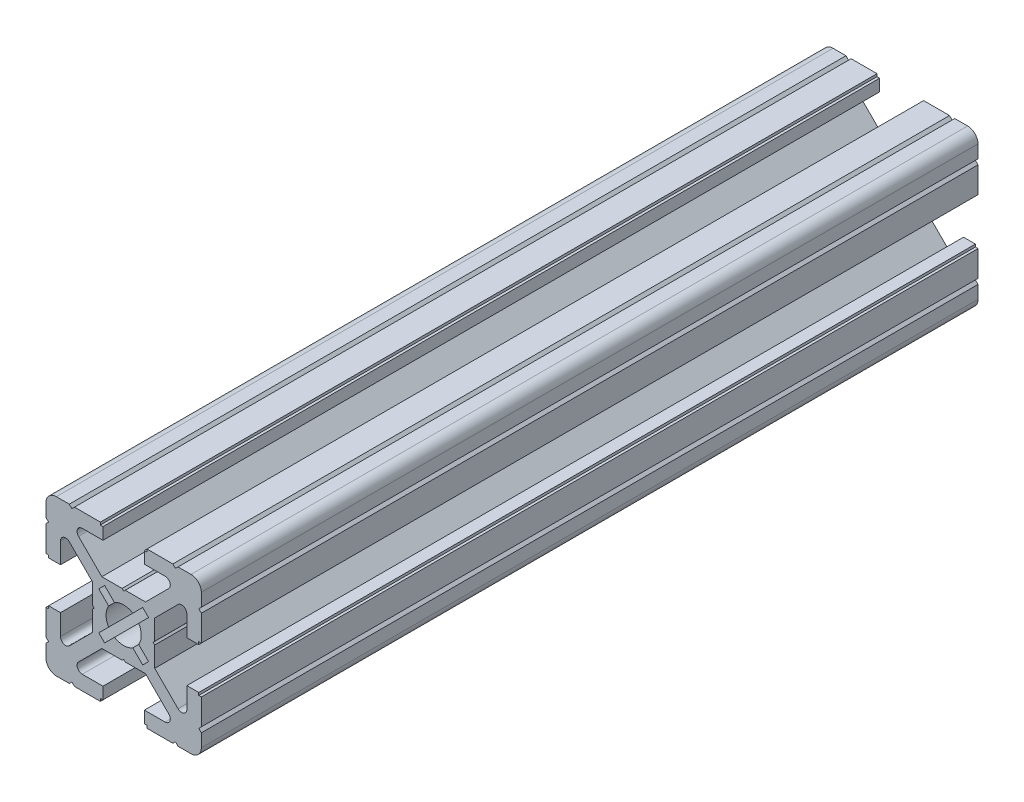
SolidWorks part; units mm, degrees
material "1060 Alloy"
ref_plane "Front" through (0, 0, 0) normal (0, 0, 1) x (1, 0, 0)
ref_plane "Top" through (0, 0, 0) normal (0, 1, 0) x (1, 0, 0)
ref_plane "Right" through (0, 0, 0) normal (1, 0, 0) x (0, 0, -1)
sketch "Sketch1" plane through (0, 0, 0) normal (0, 0, 1) x (1, 0, 0)
  line L0 (-2.9023, 1.771) -> (-4.8083, 3.677)
  line L1 (-4.8083, 3.677) -> (-3.677, 4.8083)
  line L2 (-3.677, 4.8083) -> (-1.771, 2.9023)
  line L3 (1.771, 2.9023) -> (3.677, 4.8083)
  line L4 (3.677, 4.8083) -> (4.8083, 3.677)
  line L5 (4.8083, 3.677) -> (2.9023, 1.771)
  line L6 (2.9023, -1.771) -> (4.8083, -3.677)
  line L7 (4.8083, -3.677) -> (3.677, -4.8083)
  line L8 (3.677, -4.8083) -> (1.771, -2.9023)
  line L9 (-1.771, -2.9023) -> (-3.677, -4.8083)
  line L10 (-3.677, -4.8083) -> (-4.8083, -3.677)
  line L11 (-4.8083, -3.677) -> (-2.9023, -1.771)
  line L12 (13, 15) -> (10.5, 15)
  line L13 (10.5, 15) -> (10, 14.5)
  line L14 (10, 14.5) -> (9.5, 15)
  line L15 (9.5, 15) -> (4.5, 15)
  line L16 (4.5, 15) -> (4.5, 14.5)
  line L17 (4.5, 14.5) -> (4, 14.5)
  line L18 (4, 14.5) -> (4, 12.2)
  line L19 (4, 12.2) -> (8, 12.2)
  line L20 (8.7071, 10.4929) -> (4.2142, 6)
  line L21 (4.2142, 6) -> (0.3125, 6)
  line L22 (0.3125, 6) -> (0, 5.7)
  line L23 (0, 5.7) -> (-0.3125, 6)
  line L24 (-0.3125, 6) -> (-4.2142, 6)
  line L25 (-4.2142, 6) -> (-8.7071, 10.4929)
  line L26 (-8, 12.2) -> (-4, 12.2)
  line L27 (-4, 12.2) -> (-4, 14.5)
  line L28 (-4, 14.5) -> (-4.5, 14.5)
  line L29 (-4.5, 14.5) -> (-4.5, 15)
  line L30 (-4.5, 15) -> (-9.5, 15)
  line L31 (-9.5, 15) -> (-10, 14.5)
  line L32 (-10, 14.5) -> (-10.5, 15)
  line L33 (-10.5, 15) -> (-13, 15)
  line L34 (-15, 13) -> (-15, 10.5)
  line L35 (-15, 10.5) -> (-14.5, 10)
  line L36 (-14.5, 10) -> (-15, 9.5)
  line L37 (-15, 9.5) -> (-15, 4.5)
  line L38 (-15, 4.5) -> (-14.5, 4.5)
  line L39 (-14.5, 4.5) -> (-14.5, 4)
  line L40 (-14.5, 4) -> (-12.2, 4)
  line L41 (-12.2, 4) -> (-12.2, 8)
  line L42 (-10.4929, 8.7071) -> (-6, 4.2142)
  line L43 (-6, 4.2142) -> (-6, 0.3125)
  line L44 (-6, 0.3125) -> (-5.7, 0)
  line L45 (-5.7, 0) -> (-6, -0.3125)
  line L46 (-6, -0.3125) -> (-6, -4.2142)
  line L47 (-6, -4.2142) -> (-10.4929, -8.7071)
  line L48 (-12.2, -8) -> (-12.2, -4)
  line L49 (-12.2, -4) -> (-14.5, -4)
  line L50 (-14.5, -4) -> (-14.5, -4.5)
  line L51 (-14.5, -4.5) -> (-15, -4.5)
  line L52 (-15, -4.5) -> (-15, -9.5)
  line L53 (-15, -9.5) -> (-14.5, -10)
  line L54 (-14.5, -10) -> (-15, -10.5)
  line L55 (-15, -10.5) -> (-15, -13)
  line L56 (-13, -15) -> (-10.4899, -15)
  line L57 (-10.4899, -15) -> (-9.9899, -14.5)
  line L58 (-9.9899, -14.5) -> (-9.5, -15)
  line L59 (-9.5, -15) -> (-4.5, -15)
  line L60 (-4.5, -15) -> (-4.5, -14.5)
  line L61 (-4.5, -14.5) -> (-4, -14.5)
  line L62 (-4, -14.5) -> (-4, -12.2)
  line L63 (-4, -12.2) -> (-8, -12.2)
  line L64 (-8.7071, -10.4929) -> (-4.2142, -6)
  line L65 (-4.2142, -6) -> (-0.3125, -6)
  line L66 (-0.3125, -6) -> (0, -5.7)
  line L67 (0, -5.7) -> (0.3125, -6)
  line L68 (0.3125, -6) -> (4.2142, -6)
  line L69 (4.2142, -6) -> (8.7071, -10.4929)
  line L70 (8, -12.2) -> (4, -12.2)
  line L71 (4, -12.2) -> (4, -14.5)
  line L72 (4, -14.5) -> (4.5, -14.5)
  line L73 (4.5, -14.5) -> (4.5, -15)
  line L74 (4.5, -15) -> (9.5, -15)
  line L75 (9.5, -15) -> (10, -14.5)
  line L76 (10, -14.5) -> (10.5, -15)
  line L77 (10.5, -15) -> (13, -15)
  line L78 (15, -13) -> (15, -10.5)
  line L79 (15, -10.5) -> (14.5, -10)
  line L80 (14.5, -10) -> (15, -9.5)
  line L81 (15, -9.5) -> (15, -4.5)
  line L82 (15, -4.5) -> (14.5, -4.5)
  line L83 (14.5, -4.5) -> (14.5, -4)
  line L84 (14.5, -4) -> (12.2, -4)
  line L85 (12.2, -4) -> (12.2, -8)
  line L86 (10.4929, -8.7071) -> (6, -4.2142)
  line L87 (6, -4.2142) -> (6, -0.3125)
  line L88 (6, -0.3125) -> (5.7, 0)
  line L89 (5.7, 0) -> (6, 0.3125)
  line L90 (6, 0.3125) -> (6, 4.2142)
  line L91 (6, 4.2142) -> (10.4929, 8.7071)
  line L92 (12.2, 8) -> (12.2, 4)
  line L93 (12.2, 4) -> (14.5, 4)
  line L94 (14.5, 4) -> (14.5, 4.5)
  line L95 (14.5, 4.5) -> (15, 4.5)
  line L96 (15, 4.5) -> (15, 9.5)
  line L97 (15, 9.5) -> (14.5, 10)
  line L98 (14.5, 10) -> (15, 10.5)
  line L99 (15, 10.5) -> (15, 13)
  arc A0 (-1.771, 2.9023) -> (1.771, 2.9023) centre (0, 0) cw
  arc A1 (2.9023, 1.771) -> (2.9023, -1.771) centre (0, 0) cw
  arc A2 (1.771, -2.9023) -> (-1.771, -2.9023) centre (0, 0) cw
  arc A3 (-2.9023, -1.771) -> (-2.9023, 1.771) centre (0, 0) cw
  arc A4 (8, 12.2) -> (8.7071, 10.4929) centre (8, 11.2) cw
  arc A5 (-8.7071, 10.4929) -> (-8, 12.2) centre (-8, 11.2) cw
  arc A6 (-13, 15) -> (-15, 13) centre (-13, 13) ccw
  arc A7 (-12.2, 8) -> (-10.4929, 8.7071) centre (-11.2, 8) cw
  arc A8 (-10.4929, -8.7071) -> (-12.2, -8) centre (-11.2, -8) cw
  arc A9 (-15, -13) -> (-13, -15) centre (-13, -13) ccw
  arc A10 (-8, -12.2) -> (-8.7071, -10.4929) centre (-8, -11.2) cw
  arc A11 (8.7071, -10.4929) -> (8, -12.2) centre (8, -11.2) cw
  arc A12 (13, -15) -> (15, -13) centre (13, -13) ccw
  arc A13 (12.2, -8) -> (10.4929, -8.7071) centre (11.2, -8) cw
  arc A14 (10.4929, 8.7071) -> (12.2, 8) centre (11.2, 8) cw
  arc A15 (15, 13) -> (13, 15) centre (13, 13) ccw
  dimension "D3" = 3.4
  dimension "D7" = 2
  dimension "D1" = 30
  dimension "D2" = 30
  dimension "D4" = 9
  dimension "D5" = 9
  dimension "D6" = 8
  dimension "D8" = 2.8
extrude "Boss-Extrude1" add sketch "Sketch1" along normal blind 150
